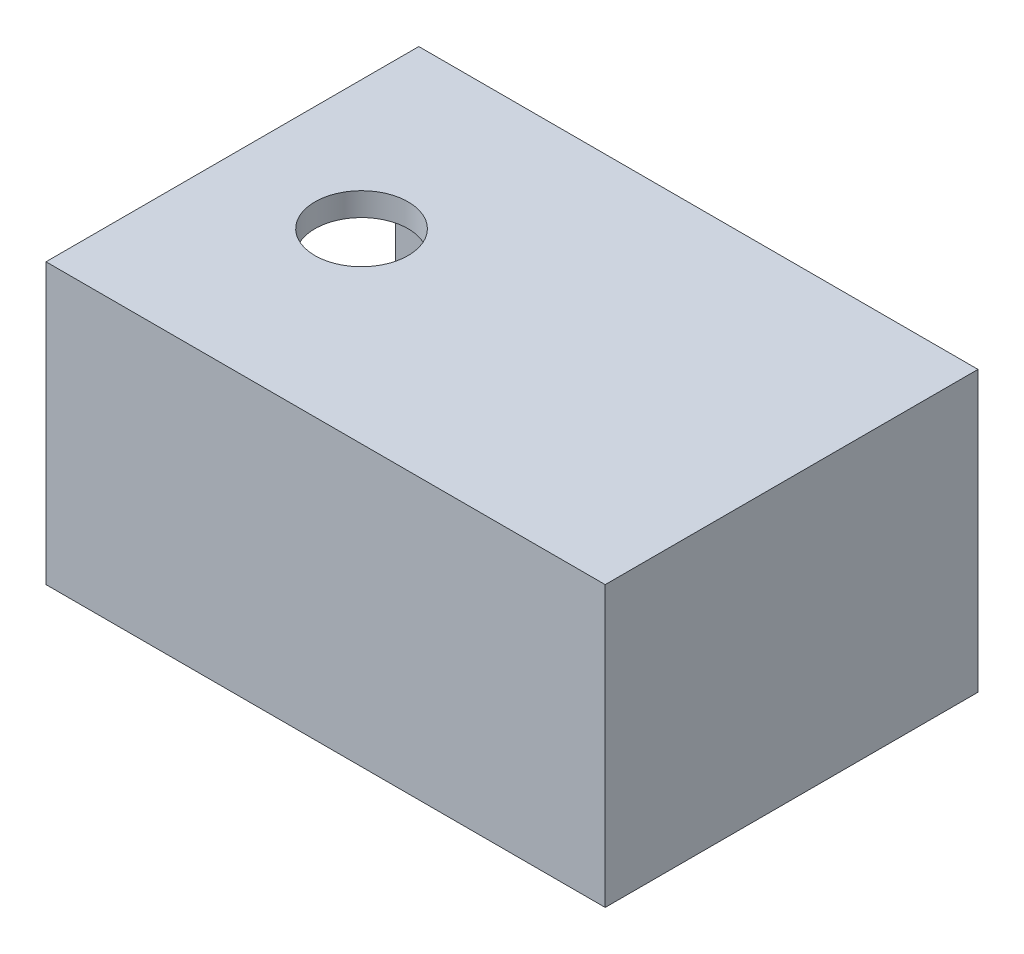
SolidWorks part; units mm, degrees
ref_plane "Front Plane" through (0, 0, 0) normal (0, 0, 1) x (1, 0, 0)
ref_plane "Top Plane" through (0, 0, 0) normal (0, 1, 0) x (1, 0, 0)
ref_plane "Right Plane" through (0, 0, 0) normal (1, 0, 0) x (0, 0, -1)
sketch "Sketch1" plane through (0, 0, 0) normal (0, 1, 0) x (1, 0, 0)
  line L1 (-40.6105, -17.5629) -> (19.3895, -17.5629)
  line L2 (-40.6105, -17.5629) -> (-40.6105, 22.4371)
  line L3 (-40.6105, 22.4371) -> (19.3895, 22.4371)
  line L4 (19.3895, -17.5629) -> (19.3895, 22.4371)
  dimension "D1" = 60
  dimension "D2" = 40
extrude "Boss-Extrude1" add sketch "Sketch1" along normal blind 30
sketch "Sketch2" plane through (-40.6105, 0, 0) normal (-1, 0, 0) x (0, 0, 1)
  line L0 (-19.9371, 2.5) -> (-19.9371, 27.5)
  line L1 (-22.4371, 0) -> (17.5629, 0)
  line L2 (-22.4371, 0) -> (-22.4371, 30)
  line L3 (-22.4371, 30) -> (17.5629, 30)
  line L4 (17.5629, 0) -> (17.5629, 30)
  line L5 (-19.9371, 27.5) -> (15.0629, 27.5)
  line L6 (15.0629, 2.5) -> (15.0629, 27.5)
  line L7 (-19.9371, 2.5) -> (15.0629, 2.5)
  dimension "D1" = 2.5
extrude "Cut-Extrude1" cut sketch "Sketch2" against normal blind 57.5 flip side to cut
sketch "Sketch3" plane through (0, 30, 0) normal (0, 1, 0) x (1, 0, 0)
  circle A0 centre (-26.7547, 2.4371) radius 2.5
extrude "Cut-Extrude2" cut sketch "Sketch3" against normal blind 57.5
fillet "Fillet1" radius 1 1 edges at (-26.7547, 2.5, -4.9371)
sketch "Sketch4" plane through (0, 30, 0) normal (0, 1, 0) x (1, 0, 0)
  circle A0 centre (-26.7547, 2.4371) radius 5
extrude "Cut-Extrude3" cut sketch "Sketch4" against normal blind 20
